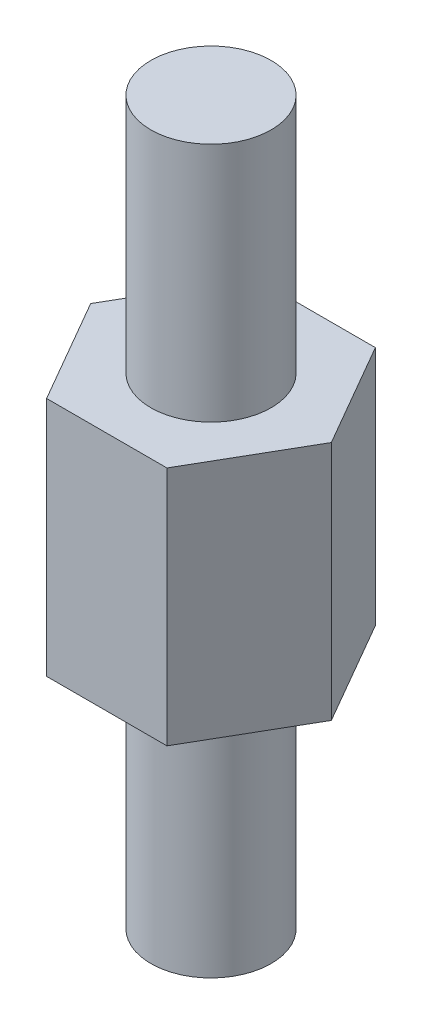
SolidWorks part; units mm, degrees
ref_plane "前视基准面" through (0, 0, 0) normal (0, 0, 1) x (1, 0, 0)
ref_plane "上视基准面" through (0, 0, 0) normal (0, 1, 0) x (1, 0, 0)
ref_plane "右视基准面" through (0, 0, 0) normal (1, 0, 0) x (0, 0, -1)
other "Configuration Table"
sketch "草图1" plane through (0, 0, 0) normal (0, 1, 0) x (1, 0, 0)
  line L1 (3, 0) -> (1.5, 2.5981)
  line L2 (1.5, 2.5981) -> (-1.5, 2.5981)
  line L3 (-1.5, 2.5981) -> (-3, 0)
  line L4 (-3, 0) -> (-1.5, -2.5981)
  line L5 (-1.5, -2.5981) -> (1.5, -2.5981)
  line L6 (1.5, -2.5981) -> (3, 0)
  circle A0 centre (0, 0) radius 2.5981 construction
  dimension "D1" = 3
extrude "凸台-拉伸1" add sketch "草图1" along normal blind 6
sketch "草图2" plane through (0, 6, 0) normal (0, 1, 0) x (1, 0, 0)
  circle A0 centre (0, 0) radius 1.5
  dimension "D1" = 3
extrude "凸台-拉伸2" add sketch "草图2" along normal blind 6
sketch "草图3" plane through (0, 0, 0) normal (0, -1, 0) x (1, 0, 0)
  circle A1 centre (0, 0) radius 1.5
  circle A2 centre (0, 0) radius 1.5
  dimension "D1" = 0
extrude "凸台-拉伸3" add sketch "草图3" along normal blind 6
